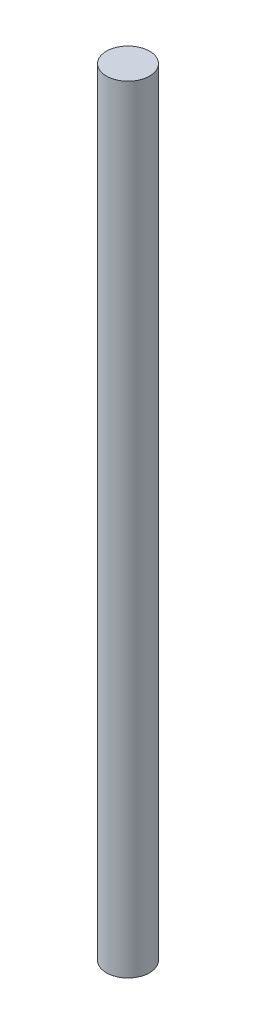
SolidWorks part; units mm, degrees
ref_plane "前视基准面" through (0, 0, 0) normal (0, 0, 1) x (1, 0, 0)
ref_plane "上视基准面" through (0, 0, 0) normal (0, 1, 0) x (1, 0, 0)
ref_plane "右视基准面" through (0, 0, 0) normal (1, 0, 0) x (0, 0, -1)
sketch "草图1" plane through (0, 0, 0) normal (0, 1, 0) x (1, 0, 0)
  circle A0 centre (0, 0) radius 15
  dimension "D1" = 30
extrude "凸台-拉伸1" add sketch "草图1" along normal blind 540
